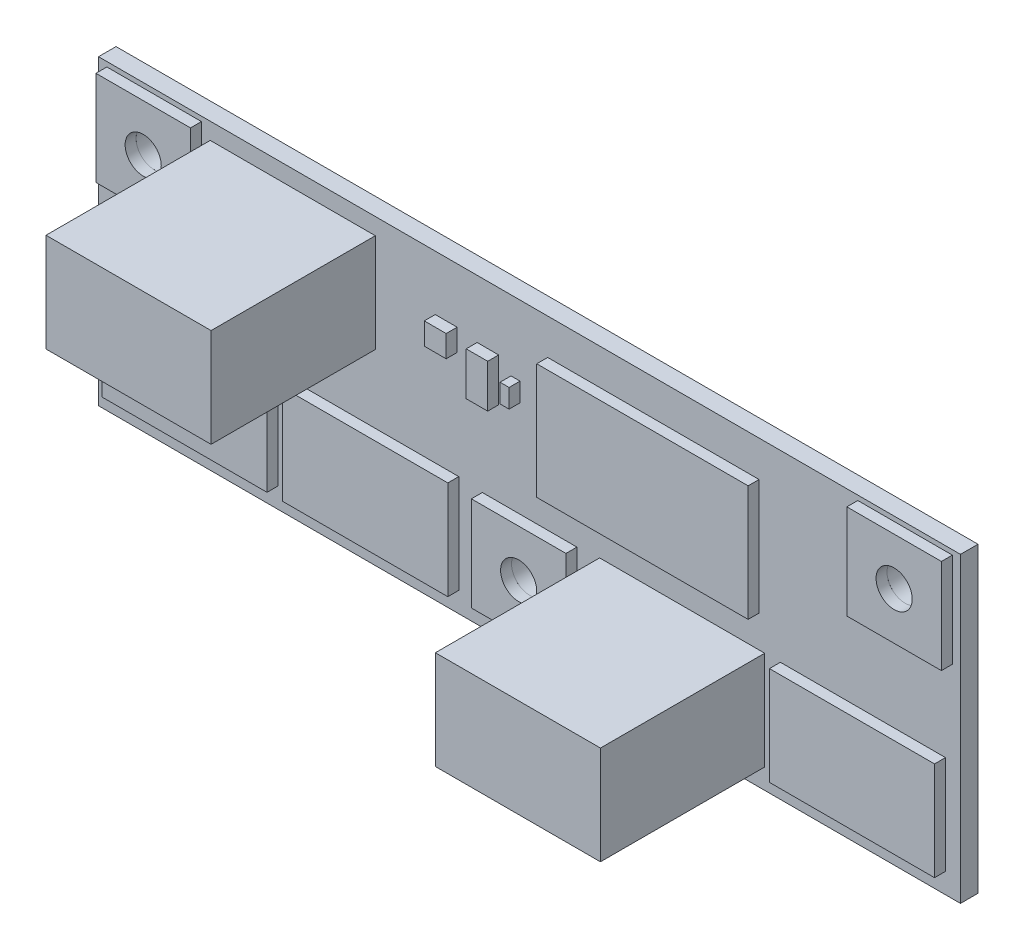
SolidWorks part; units mm, degrees
ref_plane "Front Plane" through (0, 0, 0) normal (0, 0, 1) x (1, 0, 0)
ref_plane "Top Plane" through (0, 0, 0) normal (0, 1, 0) x (1, 0, 0)
ref_plane "Right Plane" through (0, 0, 0) normal (1, 0, 0) x (0, 0, -1)
sketch "Sketch1" plane through (0, 0, 0) normal (0, 0, 1) x (1, 0, 0)
  line L0 (0, 0) -> (78.72, 0)
  line L1 (78.72, 0) -> (78.72, 27.61)
  line L2 (78.72, 27.61) -> (0, 27.61)
  line L3 (0, 27.61) -> (0, 0)
extrude "BOARD" add sketch "Sketch1" along normal blind 1.6 separate body
ref_plane "Plane1" through (0, 0, 1.6) normal (0, 0, 1) x (1, 0, 0)
sketch "Sketch2" plane through (0, 0, 1.6) normal (0, 0, 1) x (1, 0, 0)
  line L0 (38.4945, 19.481) -> (37.6674, 19.481)
  line L1 (37.6674, 19.481) -> (37.6674, 21.1971)
  line L2 (37.6674, 21.1971) -> (38.4945, 21.1971)
  line L3 (38.4945, 21.1971) -> (38.4945, 19.481)
extrude "C0402-1" add sketch "Sketch2" along normal blind 1 separate body
sketch "Sketch3" plane through (0, 0, 1.6) normal (0, 0, 1) x (1, 0, 0)
  line L0 (0.762, 27.178) -> (9.398, 27.178)
  line L1 (9.398, 27.178) -> (9.398, 18.542)
  line L2 (9.398, 18.542) -> (0.762, 18.542)
  line L3 (0.762, 18.542) -> (0.762, 27.178)
extrude "3_3-1" add sketch "Sketch3" along normal blind 1 separate body
sketch "Sketch4" plane through (0, 0, 1.6) normal (0, 0, 1) x (1, 0, 0)
  line L0 (69.342, 27.178) -> (77.978, 27.178)
  line L1 (77.978, 27.178) -> (77.978, 18.542)
  line L2 (77.978, 18.542) -> (69.342, 18.542)
  line L3 (69.342, 18.542) -> (69.342, 27.178)
extrude "3_3-2" add sketch "Sketch4" along normal blind 1 separate body
sketch "Sketch5" plane through (0, 0, 1.6) normal (0, 0, 1) x (1, 0, 0)
  line L0 (35.052, 10.668) -> (43.688, 10.668)
  line L1 (43.688, 10.668) -> (43.688, 2.032)
  line L2 (43.688, 2.032) -> (35.052, 2.032)
  line L3 (35.052, 2.032) -> (35.052, 10.668)
extrude "3_3-3" add sketch "Sketch5" along normal blind 1 separate body
sketch "Sketch6" plane through (0, 0, 1.6) normal (0, 0, 1) x (1, 0, 0)
  line L0 (60.325, 24.3332) -> (60.325, 13.7668)
  line L1 (60.325, 13.7668) -> (41.021, 13.7668)
  line L2 (41.021, 13.7668) -> (41.021, 24.3332)
  line L3 (41.021, 24.3332) -> (60.325, 24.3332)
extrude "TO220H-1" add sketch "Sketch6" along normal blind 1 separate body
sketch "Sketch7" plane through (0, 0, 1.6) normal (0, 0, 1) x (1, 0, 0)
  line L0 (34.577, 18.347) -> (34.577, 22.293)
  line L1 (34.577, 22.293) -> (36.543, 22.293)
  line L2 (36.543, 22.293) -> (36.543, 18.347)
  line L3 (36.543, 18.347) -> (34.577, 18.347)
extrude "R0805-1" add sketch "Sketch7" along normal blind 1 separate body
sketch "Sketch8" plane through (0, 0, 1.6) normal (0, 0, 1) x (1, 0, 0)
  line L0 (10.2038, 26.09) -> (25.28, 26.09)
  line L1 (25.28, 26.09) -> (25.28, 17.09)
  line L2 (25.28, 17.09) -> (10.2038, 17.09)
  line L3 (10.2038, 17.09) -> (10.2038, 26.09)
extrude "1935789-1" add sketch "Sketch8" along normal blind 15 separate body
sketch "Sketch9" plane through (0, 0, 1.6) normal (0, 0, 1) x (1, 0, 0)
  line L0 (17.8238, 10.85) -> (32.9, 10.85)
  line L1 (32.9, 10.85) -> (32.9, 1.85)
  line L2 (32.9, 1.85) -> (17.8238, 1.85)
  line L3 (17.8238, 1.85) -> (17.8238, 10.85)
extrude "1935789-2" add sketch "Sketch9" along normal blind 1 separate body
sketch "Sketch10" plane through (0, 0, 1.6) normal (0, 0, 1) x (1, 0, 0)
  line L0 (45.7638, 10.85) -> (60.84, 10.85)
  line L1 (60.84, 10.85) -> (60.84, 1.85)
  line L2 (60.84, 1.85) -> (45.7638, 1.85)
  line L3 (45.7638, 1.85) -> (45.7638, 10.85)
extrude "1935789-3" add sketch "Sketch10" along normal blind 15 separate body
sketch "Sketch11" plane through (0, 0, 1.6) normal (0, 0, 1) x (1, 0, 0)
  line L0 (1.3138, 10.85) -> (16.39, 10.85)
  line L1 (16.39, 10.85) -> (16.39, 1.85)
  line L2 (16.39, 1.85) -> (1.3138, 1.85)
  line L3 (1.3138, 1.85) -> (1.3138, 10.85)
extrude "1935789-4" add sketch "Sketch11" along normal blind 1 separate body
sketch "Sketch12" plane through (0, 0, 0) normal (0, 0, 1) x (1, 0, 0)
  line L0 (21.32, 15.51) -> (21.32, 17.51)
  line L1 (21.32, 17.51) -> (19.32, 17.51)
  line L2 (19.32, 17.51) -> (19.32, 15.51)
  line L3 (19.32, 15.51) -> (21.32, 15.51)
extrude "2920L400_15MR-1" add sketch "Sketch12" against normal blind 1 separate body
sketch "Sketch13" plane through (0, 0, 0) normal (0, 0, 1) x (1, 0, 0)
  line L0 (49.26, 15.51) -> (49.26, 17.51)
  line L1 (49.26, 17.51) -> (47.26, 17.51)
  line L2 (47.26, 17.51) -> (47.26, 15.51)
  line L3 (47.26, 15.51) -> (49.26, 15.51)
extrude "2920L400_15MR-2" add sketch "Sketch13" against normal blind 1 separate body
sketch "Sketch14" plane through (0, 0, 0) normal (0, 0, 1) x (1, 0, 0)
  line L0 (4.81, 15.51) -> (4.81, 17.51)
  line L1 (4.81, 17.51) -> (2.81, 17.51)
  line L2 (2.81, 17.51) -> (2.81, 15.51)
  line L3 (2.81, 15.51) -> (4.81, 15.51)
extrude "2920L400_15MR-3" add sketch "Sketch14" against normal blind 1 separate body
sketch "Sketch15" plane through (0, 0, 0) normal (0, 0, 1) x (1, 0, 0)
  line L0 (65.77, 15.51) -> (65.77, 17.51)
  line L1 (65.77, 17.51) -> (63.77, 17.51)
  line L2 (63.77, 17.51) -> (63.77, 15.51)
  line L3 (63.77, 15.51) -> (65.77, 15.51)
extrude "2920L400_15MR-4" add sketch "Sketch15" against normal blind 1 separate body
sketch "Sketch16" plane through (0, 0, 1.6) normal (0, 0, 1) x (1, 0, 0)
  line L0 (62.2738, 10.85) -> (77.35, 10.85)
  line L1 (77.35, 10.85) -> (77.35, 1.85)
  line L2 (77.35, 1.85) -> (62.2738, 1.85)
  line L3 (62.2738, 1.85) -> (62.2738, 10.85)
extrude "1935789-5" add sketch "Sketch16" along normal blind 1 separate body
sketch "Sketch17" plane through (0, 0, 1.6) normal (0, 0, 1) x (1, 0, 0)
  line L0 (30.75, 20.59) -> (30.75, 22.59)
  line L1 (30.75, 22.59) -> (32.75, 22.59)
  line L2 (32.75, 22.59) -> (32.75, 20.59)
  line L3 (32.75, 20.59) -> (30.75, 20.59)
extrude "PDM_2019_REVB_MIC4416YM4-TR-1" add sketch "Sketch17" along normal blind 1 separate body
sketch "Sketch18" plane through (0, 0, 2.6) normal (0, 0, 1) x (1, 0, 0)
  line L0 (0.762, 27.178) -> (9.398, 18.542) construction
  line L1 (9.398, 18.542) -> (9.398, 27.178) construction
  line L2 (9.398, 27.178) -> (0.762, 18.542) construction
  circle A0 centre (5.08, 22.86) radius 1.65
extrude "Cut-Extrude1" cut sketch "Sketch18" against normal blind 10.16
sketch "Sketch19" plane through (0, 0, 2.6) normal (0, 0, 1) x (1, 0, 0)
  line L0 (35.052, 10.668) -> (43.688, 2.032) construction
  circle A0 centre (39.37, 6.35) radius 1.65
extrude "Cut-Extrude2" cut sketch "Sketch19" against normal blind 10.16
sketch "Sketch20" plane through (0, 0, 2.6) normal (0, 0, 1) x (1, 0, 0)
  line L0 (69.342, 27.178) -> (77.978, 18.542) construction
  circle A0 centre (73.66, 22.86) radius 1.65
extrude "Cut-Extrude3" cut sketch "Sketch20" against normal blind 10.16
